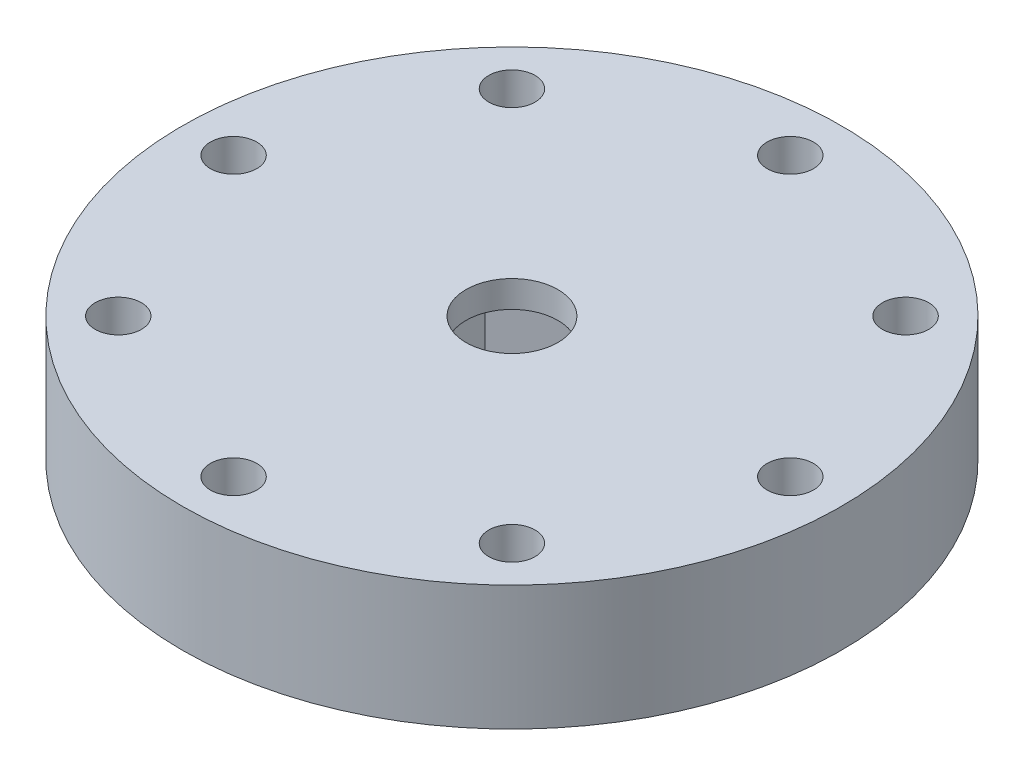
SolidWorks part; units mm, degrees
ref_plane "Front Plane" through (0, 0, 0) normal (0, 0, 1) x (1, 0, 0)
ref_plane "Top Plane" through (0, 0, 0) normal (0, 1, 0) x (1, 0, 0)
ref_plane "Right Plane" through (0, 0, 0) normal (1, 0, 0) x (0, 0, -1)
sketch "Sketch1" plane through (0, 0, 0) normal (0, 1, 0) x (1, 0, 0)
  circle A0 centre (0, 0) radius 37
  circle A1 centre (0, 0) radius 31.25 construction
  circle A2 centre (0, 31.25) radius 1
  circle A3 centre (22.0971, 22.0971) radius 1
  circle A4 centre (31.25, 0) radius 1
  circle A5 centre (22.0971, -22.0971) radius 1
  circle A6 centre (0, -31.25) radius 1
  circle A7 centre (-22.0971, -22.0971) radius 1
  circle A8 centre (-31.25, 0) radius 1
  circle A9 centre (-22.0971, 22.0971) radius 1
  dimension "D1" = 74
  dimension "D2" = 62.5
  dimension "D4" = 2
  dimension "D3" = 8
extrude "Boss-Extrude1" add sketch "Sketch1" along normal blind 14
hole_wizard "CBORE for M2.5 Hex Socket Head Cap Screw1" positions "Sketch2" profile "Sketch3" counterbore size "M2.5" standard "ISO"
sketch "Sketch2" plane through (0, 14, 0) normal (0, 1, 0) x (1, 0, 0)
  point P0 (-31.25, 0)
  point P3 (-22.0971, -22.0971)
  point P6 (0, -31.25)
  point P9 (22.0971, -22.0971)
  point P12 (31.25, 0)
  point P15 (22.0971, 22.0971)
  point P18 (0, 31.25)
  point P21 (-22.0971, 22.0971)
sketch "Sketch3" plane through (-31.25, 14, 0) normal (1, 0, 0) x (0, 0, 1)
  line L0 (0, 0) -> (0, 14)
  line L1 (0, 14) -> (1.45, 14)
  line L3 (1.45, 14) -> (1.45, 2.9)
  line L4 (1.45, 2.9) -> (2.75, 2.9)
  line L5 (2.75, 2.9) -> (2.75, 0)
  line L7 (2.75, 0) -> (0, 0)
  line L11 (0, -6.35) -> (0, 107.95) construction
  dimension "Thru Hole Dia." = 2.9
  dimension "Thru Hole Depth" = 14
  dimension "C'Bore Dia." = 5.5
  dimension "C'Bore Depth" = 2.9
hole_wizard "3/8 Clearance Hole1" positions "Sketch4" profile "Sketch5" hole size "3/8" standard "ANSI Inch" end condition through all
sketch "Sketch4" plane through (0, 0, 0) normal (0, -1, 0) x (-1, 0, 0)
  point P0 (0, 0)
sketch "Sketch5" plane through (0, 0, 0) normal (1, 0, 0) x (0, 0, -1)
  line L0 (0, 0) -> (0, 14)
  line L1 (0, 14) -> (5.1587, 14)
  line L2 (5.1587, 14) -> (5.1587, 0)
  line L5 (5.1587, 0) -> (0, 0)
  line L11 (0, -6.35) -> (0, 107.95) construction
  dimension "Thru Hole Dia." = 10.3175
  dimension "Thru Hole Depth" = 14
sketch "Sketch8" plane through (0, 0, 0) normal (0, -1, 0) x (1, 0, 0)
  circle A0 centre (0, 0) radius 34.1
  circle A1 centre (0, 0) radius 28.4
  circle A2 centre (0, 0) radius 22.5 construction
  dimension "D1" = 56.8
  dimension "D2" = 68.2
  dimension "D3" = 45
extrude "Cut-Extrude3" cut sketch "Sketch8" against normal blind 3
sketch "Sketch9" plane through (0, 0, 0) normal (0, -1, 0) x (1, 0, 0)
  circle A0 centre (0, 0) radius 22.5
  dimension "D1" = 45
extrude "Cut-Extrude4" cut sketch "Sketch9" against normal blind 5
sketch "Sketch7" plane through (0, 5, 0) normal (0, -1, 0) x (1, 0, 0)
  line L1 (0, 8.2489) -> (-7.1438, 4.1244)
  line L2 (-7.1438, 4.1244) -> (-7.1438, -4.1244)
  line L3 (-7.1438, -4.1244) -> (0, -8.2489)
  line L4 (0, -8.2489) -> (7.1437, -4.1244)
  line L5 (7.1437, -4.1244) -> (7.1437, 4.1244)
  line L6 (7.1437, 4.1244) -> (0, 8.2489)
  circle A0 centre (0, 0) radius 7.1438 construction
  dimension "D1" = 14.2875
extrude "Cut-Extrude2" cut sketch "Sketch7" against normal blind 6
chamfer "Chamfer1" distance 0.8 angle 45 2 edges at (0, 0, -28.4) (0, 0, -34.1)
sketch "Sketch10" plane through (0, 0, 0) normal (1, 0, 0) x (0, 0, -1)
  line L0 (32.25, 14) -> (30.25, 14) construction
  line L1 (32.25, 14) -> (30.25, 14) construction
  line L2 (31.25, 14) -> (31.25, 21.6908) construction
  line L3 (32.95, 4.6) -> (32.95, 3)
  line L4 (32.95, 3) -> (31.25, 3)
  line L5 (31.25, 3) -> (31.25, 14)
  line L6 (31.25, 14) -> (33.85, 14)
  line L7 (33.85, 14) -> (33.85, 4.6)
  line L8 (33.85, 4.6) -> (32.95, 4.6)
  line L9 (30.25, 3) -> (32.25, 3) construction
  point P6 (0, 0)
  point P11 (31.25, 1.1802)
  point P12 (0, 0)
  dimension "D1" = 3.4
  dimension "D2" = 1.6
  dimension "D3" = 5.2
revolve "Cut-Revolve1" cut sketch "Sketch10" angle 360 about L2
pattern_circular "CirPattern1" count 8 over 360 about axis through (0, 0, 0) along (0, 1, 0) of "Cut-Revolve1"
